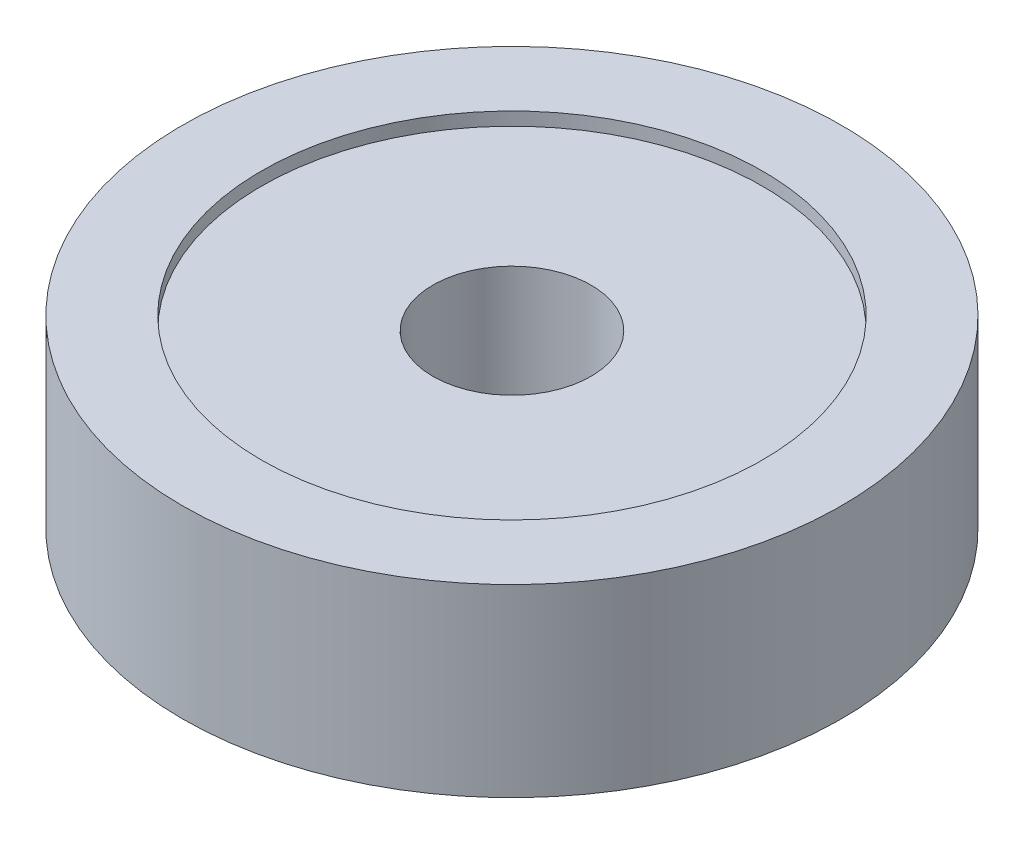
SolidWorks part; units mm, degrees
ref_plane "前视基准面" through (0, 0, 0) normal (0, 0, 1) x (1, 0, 0)
ref_plane "上视基准面" through (0, 0, 0) normal (0, 1, 0) x (1, 0, 0)
ref_plane "右视基准面" through (0, 0, 0) normal (1, 0, 0) x (0, 0, -1)
sketch "草图1" plane through (0, 0, 0) normal (0, 1, 0) x (1, 0, 0)
  circle A0 centre (0, 0) radius 3
  circle A1 centre (0, 0) radius 9.5
  dimension "D1" = 6
  dimension "D2" = 19
extrude "凸台-拉伸1" add sketch "草图1" along normal mid plane 6
sketch "草图2" plane through (0, 0, 0) normal (0, 1, 0) x (1, 0, 0)
  circle A0 centre (0, 0) radius 12.5
  circle A1 centre (0, 0) radius 9.5 construction
  circle A2 centre (0, 0) radius 9.5
  dimension "D1" = 25
extrude "凸台-拉伸2" add sketch "草图2" along normal mid plane 7 separate body
sketch "草图3" plane through (0, 3.5, 0) normal (0, 1, 0) x (1, 0, 0)
  circle A2 centre (0, 0) radius 12
  circle A3 centre (0, 0) radius 12 construction
  text T0 "https://item.taobao.com/item.htm?spm=a1z10.3-c.w4002-15226105362.54.3c39319dTIL82A&id=599558765708" font "黑体" height 1
  dimension "D1" = 0.5
extrude "切除-拉伸1" [suppressed] cut sketch "草图3" against normal blind 0.1
